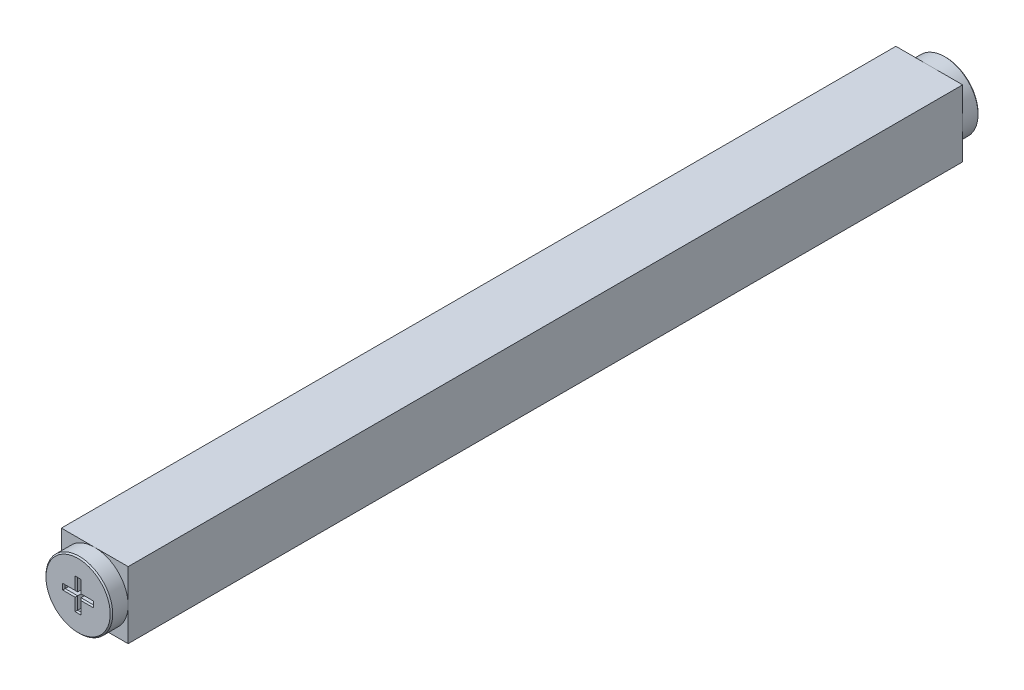
SolidWorks part; units mm, degrees
ref_plane "Front Plane" through (0, 0, 0) normal (0, 0, 1) x (1, 0, 0)
ref_plane "Top Plane" through (0, 0, 0) normal (0, 1, 0) x (1, 0, 0)
ref_plane "Right Plane" through (0, 0, 0) normal (1, 0, 0) x (0, 0, -1)
sketch "Sketch1" plane through (0, 0, 0) normal (0, 0, 1) x (1, 0, 0)
  line L1 (0, 0) -> (8, 0)
  line L2 (0, 0) -> (0, 8)
  line L3 (0, 8) -> (8, 8)
  line L4 (8, 0) -> (8, 8)
  dimension "D1" = 8
  dimension "D2" = 8
extrude "Boss-Extrude1" add sketch "Sketch1" along normal blind 50
sketch "Sketch2" plane through (0, 0, 50) normal (0, 0, 1) x (1, 0, 0)
  line L0 (4, 8) -> (4, 0) construction
  line L1 (8, 8) -> (0, 8) construction
  line L2 (0, 0) -> (8, 0) construction
  line L3 (8, 4) -> (0, 4) construction
  line L4 (8, 0) -> (8, 8) construction
  line L5 (0, 8) -> (0, 0) construction
  circle A0 centre (4, 4) radius 4
  point P14 (0, 0)
  point P15 (4, 4)
  dimension "D1" = 8
extrude "Boss-Extrude2" add sketch "Sketch2" along normal blind 2
mirror "Mirror1" of "Boss-Extrude1", "Boss-Extrude2"
sketch "Sketch3" plane through (0, 0, 52) normal (0, 0, 1) x (1, 0, 0)
  line L0 (0, 4) -> (8, 4) construction
  line L1 (4, 0) -> (4, 8) construction
  line L2 (3.8, 5.7) -> (4.2, 5.7)
  line L3 (4.2, 5.7) -> (4.2, 4.2)
  line L4 (4.2, 4.2) -> (5.7, 4.2)
  line L5 (5.7, 4.2) -> (5.7, 3.8)
  line L6 (2.3, 4.2) -> (2.3, 3.8)
  line L7 (3.8, 4.2) -> (2.3, 4.2)
  line L8 (3.8, 5.7) -> (3.8, 4.2)
  line L9 (4.2, 3.8) -> (5.7, 3.8)
  line L10 (4.2, 2.3) -> (4.2, 3.8)
  line L11 (3.8, 2.3) -> (4.2, 2.3)
  line L12 (3.8, 2.3) -> (3.8, 3.8)
  line L13 (3.8, 3.8) -> (2.3, 3.8)
  circle A0 centre (4, 4) radius 4 construction
  point P19 (4, 5.7)
  point P20 (5.7, 4)
  point P25 (2.3, 4)
  dimension "D1" = 0.2
  dimension "D2" = 0.2
  dimension "D3" = 1.5
  dimension "D4" = 1.5
extrude "Cut-Extrude1" cut sketch "Sketch3" against normal blind 2 contours L3 L4 L5 L9 L10 L11 L12 L13 L6 L7 L8 L2
mirror "Mirror3" about plane through (0, 0, 0) normal (0, 0, 1) of "Cut-Extrude1"
chamfer "Chamfer2" distance 0.15 angle 45 26 edges at (3.05, 4.2, 52) (2.3, 4, 52) (3.05, 3.8, 52) (3.8, 3.05, 52) (4, 2.3, 52) (4.2, 3.05, 52) (4.95, 3.8, 52) (5.7, 4, 52) (4.95, 4.2, 52) (4.2, 4.95, 52) (4, 5.7, 52) (3.8, 4.95, 52) (8, 4, 52) (8, 4, -52) (4.2, 4.95, -52) (4.95, 4.2, -52) (5.7, 4, -52) (4.95, 3.8, -52) (4.2, 3.05, -52) (4, 2.3, -52) (3.8, 3.05, -52) (3.05, 3.8, -52) (2.3, 4, -52) (3.05, 4.2, -52) (3.8, 4.95, -52) (4, 5.7, -52)
